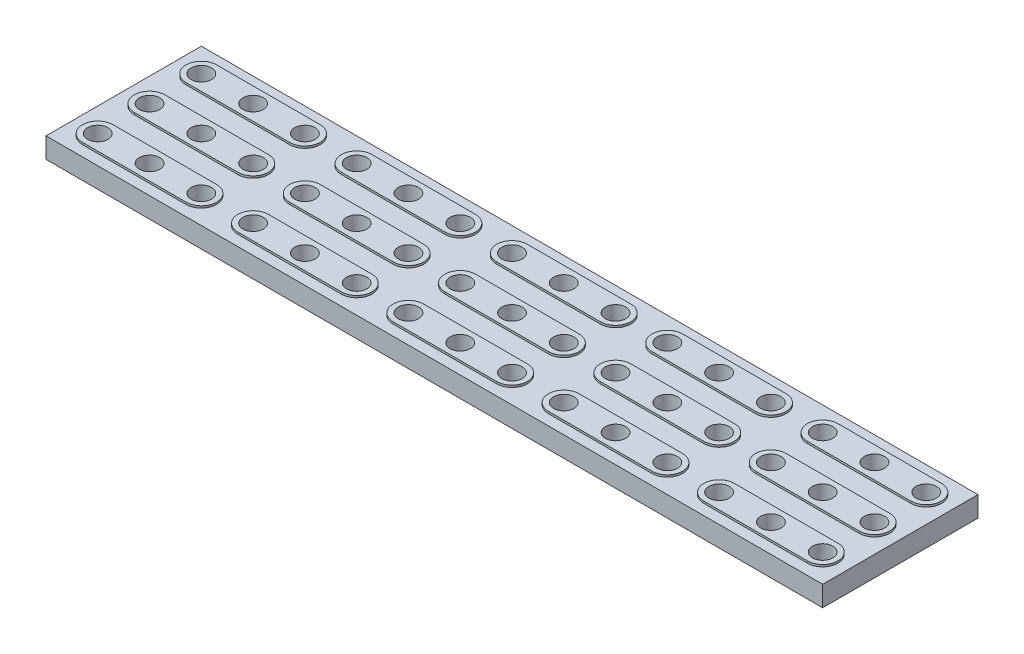
SolidWorks part; units mm, degrees
ref_plane "Front Plane" through (0, 0, 0) normal (0, 0, 1) x (1, 0, 0)
ref_plane "Top Plane" through (0, 0, 0) normal (0, 1, 0) x (1, 0, 0)
ref_plane "Right Plane" through (0, 0, 0) normal (1, 0, 0) x (0, 0, -1)
sketch "Sketch1" plane through (0, 0, 0) normal (0, 1, 0) x (1, 0, 0)
  line L0 (0, 0.75) -> (5.08, 0.75)
  line L1 (0, -0.75) -> (5.08, -0.75)
  circle A0 centre (0, 0) radius 0.5
  circle A1 centre (2.54, 0) radius 0.5
  circle A4 centre (5.08, 0) radius 0.5
  arc A6 (0, 0.75) -> (0, -0.75) centre (0, 0) ccw
  arc A7 (5.08, -0.75) -> (5.08, 0.75) centre (5.08, 0) ccw
  dimension "D2" = 3
  dimension "D1" = 1
  dimension "D4" = 1.5
  dimension "D3" = 1
extrude "Boss-Extrude1" add sketch "Sketch1" along normal blind 0.1
sketch "Sketch2" plane through (0, 0, 0) normal (0, 1, 0) x (1, 0, 0)
  line L1 (36.83, 6.35) -> (-1.27, 6.35)
  line L2 (36.83, 6.35) -> (36.83, -1.27)
  line L3 (36.83, -1.27) -> (-1.27, -1.27)
  line L4 (-1.27, 6.35) -> (-1.27, -1.27)
  dimension "D1" = 38.1
  dimension "D2" = 7.62
  dimension "D3" = 1.27
  dimension "D4" = 1.27
extrude "Boss-Extrude2" add sketch "Sketch2" against normal blind 1
pattern_linear "LPattern2" count 5 spacing 7.62 along (1, 0, 0) count 3 spacing 2.54 along (0, 0, -1) of "Boss-Extrude1"
sketch "Sketch3" plane through (0, 0, 0) normal (0, 1, 0) x (1, 0, 0)
  circle A1 centre (0, 0) radius 0.5
  circle A2 centre (2.54, 0) radius 0.5
  circle A3 centre (5.08, 0) radius 0.5
  circle A4 centre (7.62, 0) radius 0.5
  circle A5 centre (10.16, 0) radius 0.5
  circle A6 centre (12.7, 0) radius 0.5
  circle A7 centre (15.24, 0) radius 0.5
  circle A8 centre (17.78, 0) radius 0.5
  circle A9 centre (20.32, 0) radius 0.5
  circle A10 centre (22.86, 0) radius 0.5
  circle A11 centre (25.4, 0) radius 0.5
  circle A12 centre (27.94, 0) radius 0.5
  circle A13 centre (30.48, 0) radius 0.5
  circle A14 centre (33.02, 0) radius 0.5
  circle A15 centre (35.56, 0) radius 0.5
  circle A16 centre (0, 2.54) radius 0.5
  circle A17 centre (2.54, 2.54) radius 0.5
  circle A18 centre (5.08, 2.54) radius 0.5
  circle A19 centre (7.62, 2.54) radius 0.5
  circle A20 centre (10.16, 2.54) radius 0.5
  circle A21 centre (12.7, 2.54) radius 0.5
  circle A22 centre (15.24, 2.54) radius 0.5
  circle A23 centre (17.78, 2.54) radius 0.5
  circle A24 centre (20.32, 2.54) radius 0.5
  circle A25 centre (22.86, 2.54) radius 0.5
  circle A26 centre (25.4, 2.54) radius 0.5
  circle A27 centre (27.94, 2.54) radius 0.5
  circle A28 centre (30.48, 2.54) radius 0.5
  circle A29 centre (33.02, 2.54) radius 0.5
  circle A30 centre (35.56, 2.54) radius 0.5
  circle A31 centre (0, 5.08) radius 0.5
  circle A32 centre (2.54, 5.08) radius 0.5
  circle A33 centre (5.08, 5.08) radius 0.5
  circle A34 centre (7.62, 5.08) radius 0.5
  circle A35 centre (10.16, 5.08) radius 0.5
  circle A36 centre (12.7, 5.08) radius 0.5
  circle A37 centre (15.24, 5.08) radius 0.5
  circle A38 centre (17.78, 5.08) radius 0.5
  circle A39 centre (20.32, 5.08) radius 0.5
  circle A40 centre (22.86, 5.08) radius 0.5
  circle A41 centre (25.4, 5.08) radius 0.5
  circle A42 centre (27.94, 5.08) radius 0.5
  circle A43 centre (30.48, 5.08) radius 0.5
  circle A44 centre (33.02, 5.08) radius 0.5
  circle A45 centre (35.56, 5.08) radius 0.5
  dimension "D1" = 1
  dimension "D2" = 15
  dimension "D3" = 3
extrude "Cut-Extrude1" cut sketch "Sketch3" against normal through all
equation "\"Raster\"=2.54"
equation "\"D3@LPattern1\"=\"Raster\"*3"
equation "\"D2@Sketch2\"=\"Raster\"*\"Anzahl-Y\""
equation "\"D1@Sketch2\"=\"Raster\"*\"Anzahl-X\"*3"
equation "\"D3@Sketch2\"=\"Raster\"/2"
equation "\"D4@Sketch2\"=\"Raster\"/2"
equation "\"Anzahl-X\" = 5"
equation "\"Anzahl-Y\" = 3"
equation "\"D1@LPattern2\"=\"Anzahl-X\""
equation "\"D2@LPattern2\"=\"Anzahl-Y\""
equation "\"D4@LPattern2\"=\"Raster\""
equation "\"D1@Sketch3\"=\"D1@Sketch1\""
equation "\"D2@Sketch3\"=\"Anzahl-X\"*3"
equation "\"D3@Sketch3\"=\"Anzahl-Y\""
